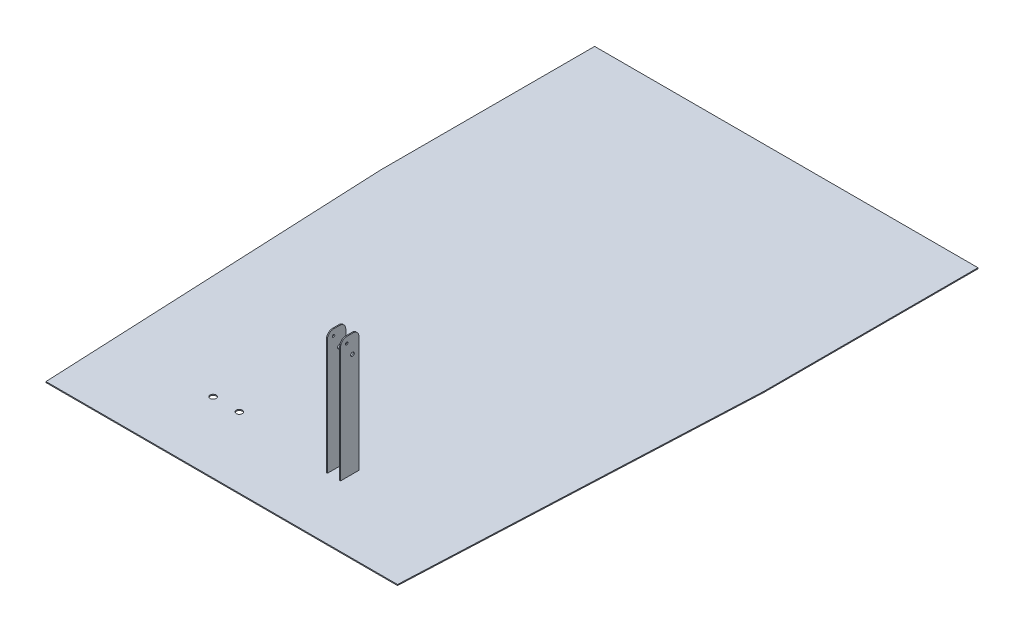
SolidWorks part; units mm, degrees
ref_plane "Front Plane" through (0, 0, 0) normal (0, 0, 1) x (1, 0, 0)
ref_plane "Top Plane" through (0, 0, 0) normal (0, 1, 0) x (1, 0, 0)
ref_plane "Right Plane" through (0, 0, 0) normal (1, 0, 0) x (0, 0, -1)
sketch "Sketch1" plane through (0, 0, 0) normal (0, 1, 0) x (1, 0, 0)
  line L0 (0, 0) -> (576, 0)
  line L1 (576, 0) -> (602.0788, 574.3)
  line L2 (602.0788, 574.3) -> (602.0788, 925.1)
  line L3 (602.0788, 925.1) -> (-26.0788, 925.1)
  line L4 (-26.0788, 925.1) -> (-26.0788, 574.3)
  line L5 (-26.0788, 574.3) -> (0, 0)
  dimension "D1" = 576
  dimension "D2" = 574.3
  dimension "D3" = 92.6
  dimension "D4" = 92.6
  dimension "D5" = 90
  dimension "D6" = 350.8
  dimension "D7" = 574.3
extrude "Boss-Extrude1" add sketch "Sketch1" along normal blind 1.6
sketch "Sketch2" plane through (0, 1.6, 0) normal (0, 1, 0) x (1, 0, 0)
  circle A0 centre (201.5, 115.4) radius 5
  circle A1 centre (158.5, 115.4) radius 5
  dimension "D3" = 10
  dimension "D4" = 10
  dimension "D5" = 43
extrude "Cut-Extrude1" cut sketch "Sketch2" against normal blind 1.6
sketch "Sketch3" plane through (0, 1.6, 0) normal (0, 1, 0) x (1, 0, 0)
  line L4 (359.2, 130.4) -> (360.8, 130.4)
  line L5 (359.2, 130.4) -> (359.2, 100.4)
  line L6 (359.2, 100.4) -> (360.8, 100.4)
  line L7 (360.8, 130.4) -> (360.8, 100.4)
  line L8 (359.2, 130.4) -> (360.8, 100.4) construction
  line L9 (359.2, 100.4) -> (360.8, 130.4) construction
  line L10 (380.8, 130.4) -> (382.4, 130.4)
  line L11 (380.8, 130.4) -> (380.8, 100.4)
  line L12 (380.8, 100.4) -> (382.4, 100.4)
  line L13 (382.4, 130.4) -> (382.4, 100.4)
  line L14 (380.8, 130.4) -> (382.4, 100.4) construction
  line L15 (380.8, 100.4) -> (382.4, 130.4) construction
  point P10 (381.6, 115.4)
  dimension "D3" = 1.6
  dimension "D4" = 1.6
  dimension "D5" = 30
  dimension "D6" = 30
  dimension "D8" = 20
extrude "Boss-Extrude2" add sketch "Sketch3" along normal blind 200
sketch "Sketch4" plane through (382.4, 0, 0) normal (1, 0, 0) x (0, 0, -1)
  line L5 (100.4, 201.6) -> (130.4, 201.6) construction
  line L6 (100.4, 201.6) -> (100.4, 1.6) construction
  circle A0 centre (110.4, 191.6) radius 2
  circle A1 centre (119.7262, 171.6) radius 3
  dimension "D1" = 4
  dimension "D2" = 6
  dimension "D3" = 30
  dimension "D4" = 19.3262
  dimension "D5" = 10
  dimension "D6" = 10
extrude "Cut-Extrude2" cut sketch "Sketch4" against normal through all
fillet "Fillet1" radius 10 4 edges at (381.6, 201.6, -100.4) (360, 201.6, -100.4) (360, 201.6, -130.4) (381.6, 201.6, -130.4)
